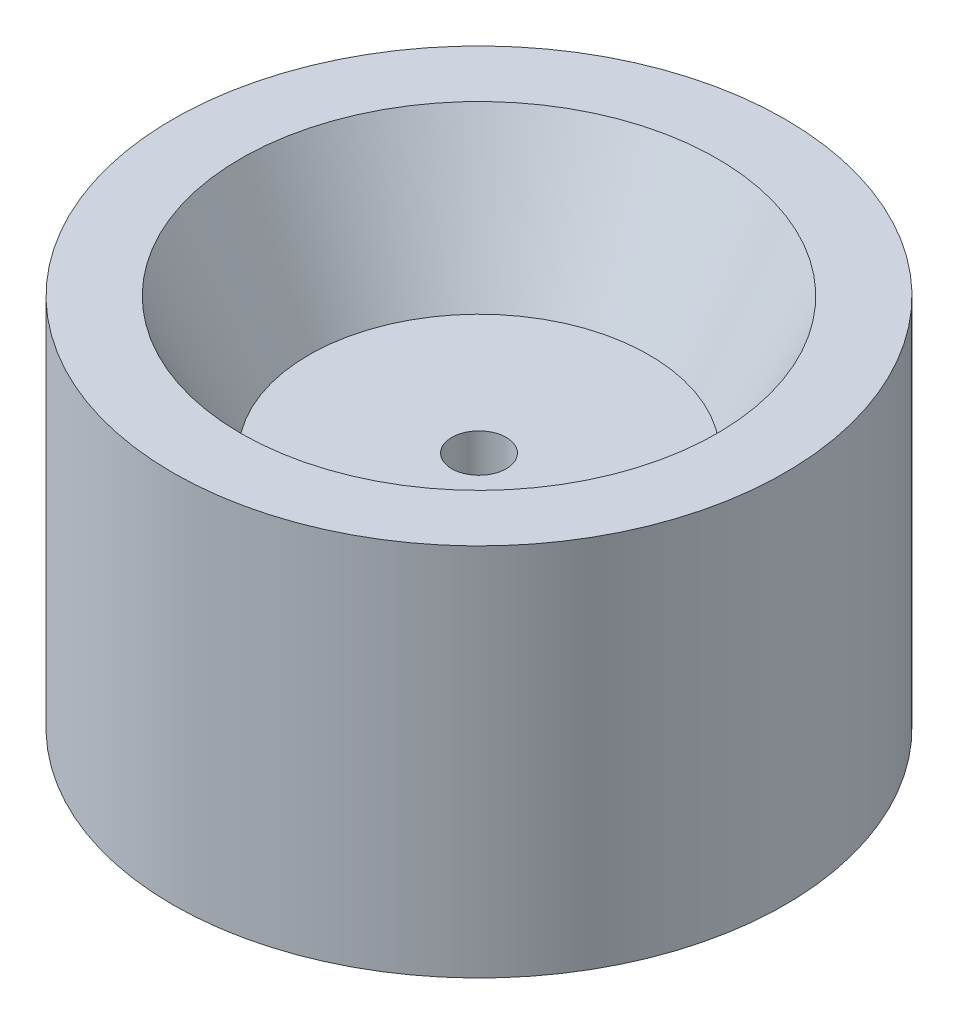
SolidWorks part; units mm, degrees
ref_plane "Front Plane" through (0, 0, 0) normal (0, 0, 1) x (1, 0, 0)
ref_plane "Top Plane" through (0, 0, 0) normal (0, 1, 0) x (1, 0, 0)
ref_plane "Right Plane" through (0, 0, 0) normal (1, 0, 0) x (0, 0, -1)
sketch "Sketch1" plane through (0, 0, 0) normal (0, 1, 0) x (1, 0, 0)
  circle A0 centre (0, 0) radius 45
  dimension "D1" = 90
extrude "Boss-Extrude1" add sketch "Sketch1" along normal blind 55
sketch "Sketch6" plane through (0, 0, 0) normal (1, 0, 0) x (0, 0, -1)
  line L0 (0, 57.0847) -> (0, 0) construction
  line L1 (0, 55) -> (0, 35)
  line L2 (-35, 55) -> (-25, 35)
  line L3 (45, 55) -> (-45, 55) construction
  line L4 (-25, 35) -> (0, 35)
  line L7 (-45, 27.5) -> (0, 27.5) construction
  line L9 (-35, 55) -> (0, 55)
  line L10 (-45, 55) -> (-45, 0) construction
  line L11 (0, 0) -> (0, 20)
  line L12 (-25, 20) -> (0, 20)
  line L13 (-35, 0) -> (0, 0)
  line L14 (-35, 0) -> (-25, 20)
  dimension "D1" = 10
  dimension "D2" = 57.0847
  dimension "D3" = 25
  dimension "D4" = 27.5
  dimension "D5" = 20
revolve "Cut-Revolve2" cut sketch "Sketch6" angle 360 about L0
sketch "Sketch7" plane through (0, 35, 0) normal (0, 1, 0) x (1, 0, 0)
  circle A1 centre (0, 0) radius 4
  point P9 (0, 0)
  dimension "D1" = 8
extrude "Cut-Extrude1" cut sketch "Sketch7" against normal up to surface (15 mm away) up to face at (0, 20, 25)
